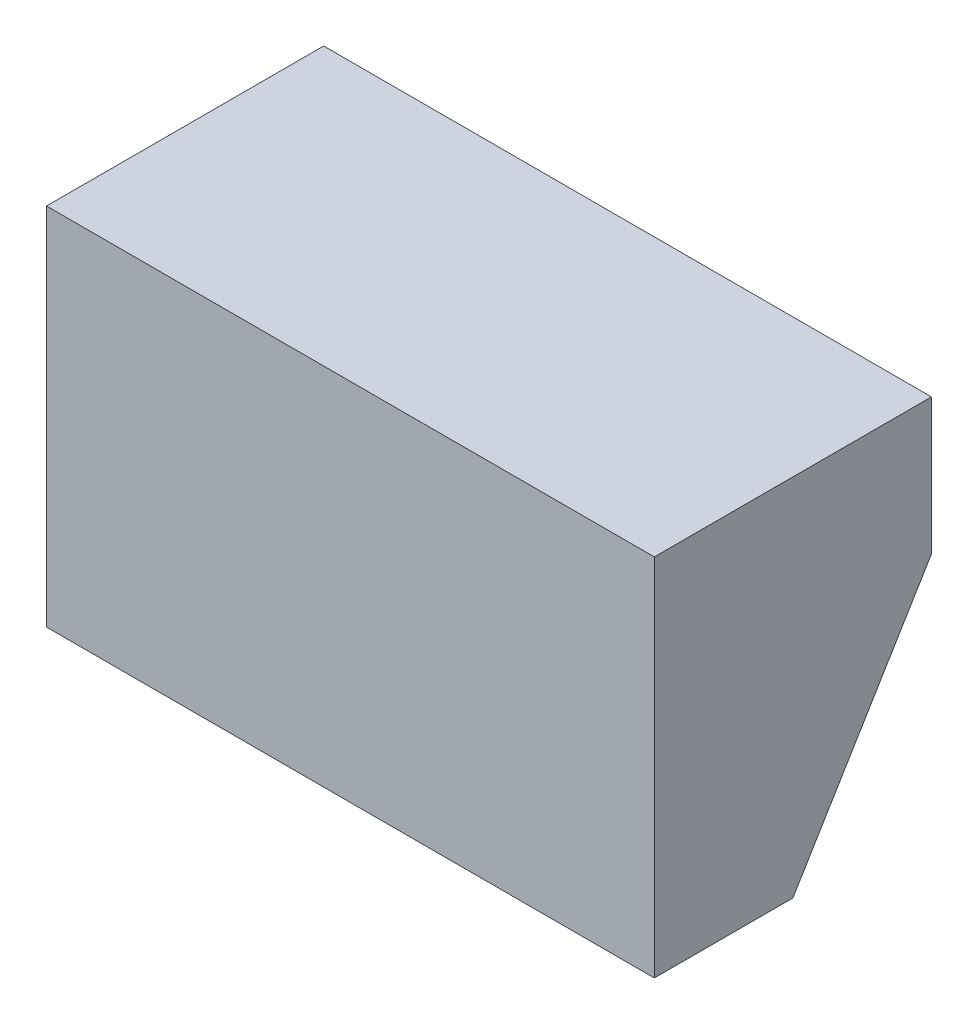
SolidWorks part; units mm, degrees
other "Defeature"
material "ABS PC"
ref_plane "前视基准面" through (0, 0, 0) normal (0, 0, 1) x (1, 0, 0)
ref_plane "上视基准面" through (0, 0, 0) normal (0, 1, 0) x (1, 0, 0)
ref_plane "右视基准面" through (0, 0, 0) normal (1, 0, 0) x (0, 0, -1)
sketch "Sketch1" plane through (0, 0, 0) normal (0, 0, 1) x (1, 0, 0)
  line L1 (-125, -75) -> (125, -75)
  line L2 (-125, -75) -> (-125, 75)
  line L3 (-125, 75) -> (125, 75)
  line L4 (125, -75) -> (125, 75)
  line L5 (-125, -75) -> (125, 75) construction
  line L6 (-125, 75) -> (125, -75) construction
  point P0 (0, 0)
  dimension "D1" = 250
  dimension "D2" = 150
extrude "Boss-Extrude1" add sketch "Sketch1" along normal blind 114
sketch "sketchCenterLine" plane through (0, 0, 114) normal (0, 0, 1) x (1, 0, 0)
  line L0 (0, 0) -> (-160.1488, 0) construction
  line L1 (-170, 12.5) -> (-115, 12.5)
  line L2 (-97.3223, 19.8223) -> (-69.467, 47.6777)
  line L3 (-51.7893, 55) -> (70, 55)
  line L4 (95, 30) -> (95, -30)
  line L5 (70, -55) -> (-51.7893, -55)
  line L6 (-69.467, -47.6777) -> (-97.3223, -19.8223)
  line L7 (-115, -12.5) -> (-170, -12.5)
  line L8 (-125, 75) -> (-125, -75) construction
  arc A0 (70, -55) -> (95, -30) centre (70, -30) ccw
  arc A1 (95, 30) -> (70, 55) centre (70, 30) ccw
  arc A2 (-115, 12.5) -> (-97.3223, 19.8223) centre (-115, 37.5) ccw
  arc A3 (-97.3223, -19.8223) -> (-115, -12.5) centre (-115, -37.5) ccw
  arc A4 (-51.7893, -55) -> (-69.467, -47.6777) centre (-51.7893, -30) cw
  arc A5 (-69.467, 47.6777) -> (-51.7893, 55) centre (-51.7893, 30) cw
  point P24 (-62.1447, -55)
  point P27 (-62.1447, 55)
  dimension "D1" = 25
  dimension "D2" = 25
  dimension "D8" = 10
  dimension "D3" = 95
  dimension "D4" = 110
  dimension "D5" = 25
  dimension "D6" = 45
  dimension "D7" = 45
sketch3d "3DSketch1"
  line L0 (125, -75, 114) -> (125, -75, 0) construction
  line L1 (125, -75, 0) -> (125, 75, 0) construction
  line L2 (-125, -75, 0) -> (125, -75, 0) construction
  point P0 (125, -75, 57)
  point P1 (125, 19.0618, 0)
  point P4 (42.2925, -75, 0)
ref_plane "Plane1" through (27.9069, -24.5383, -40.4932) normal (-0.5078, 0.4465, 0.7368) x (0.8615, 0.2632, 0.4343)
sketch "Sketch4" plane through (27.9069, -24.5383, -40.4932) normal (-0.5078, 0.4465, 0.7368) x (0.8615, 0.2632, 0.4343)
  line L1 (-16.3307, -143.8321) -> (142.4953, -143.8321)
  line L2 (-16.3307, -143.8321) -> (-16.3307, 25.2667)
  line L3 (-16.3307, 25.2667) -> (142.4953, 25.2667)
  line L4 (142.4953, -143.8321) -> (142.4953, 25.2667)
extrude "Cut-Extrude1" cut sketch "Sketch4" against normal blind 114
sketch "Sketch5" plane through (0, 0, 0) normal (0, 0, -1) x (-1, 0, 0)
  circle A0 centre (25.5219, 0) radius 21.2567
extrude "Cut-Extrude2" cut sketch "Sketch5" against normal blind 54
sketch "BaseSketch" plane through (0, 0, 0) normal (0, 0, -1) x (-1, 0, 0)
  circle A0 centre (-49.2495, 25.6076) radius 7.685
